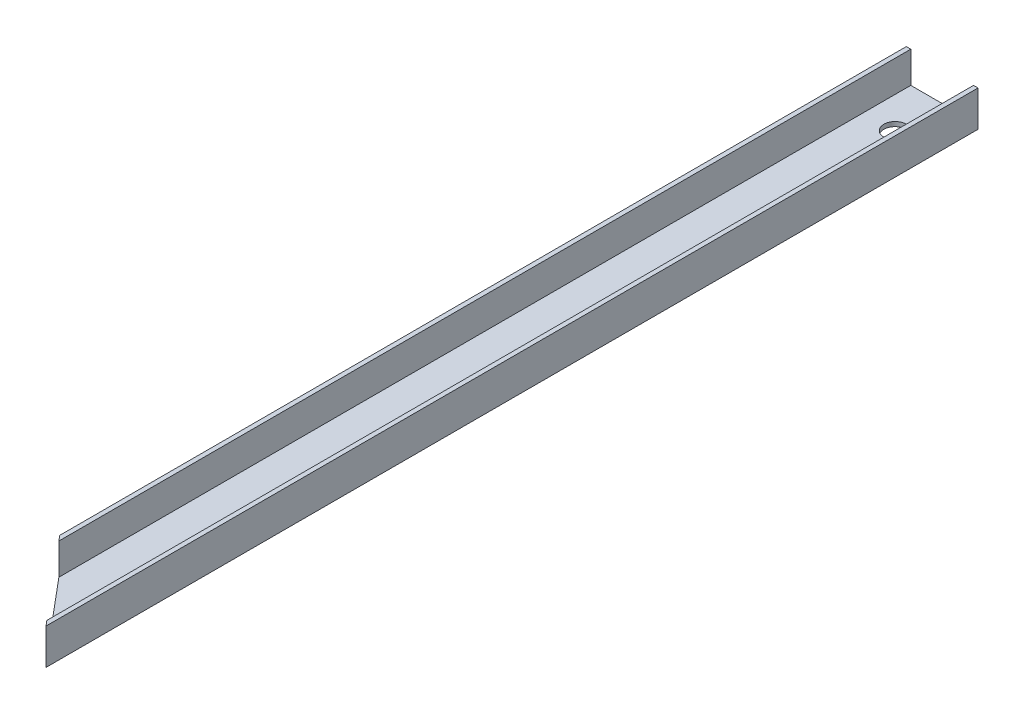
SolidWorks part; units mm, degrees
ref_plane "Front Plane" through (0, 0, 0) normal (0, 0, 1) x (1, 0, 0)
ref_plane "Top Plane" through (0, 0, 0) normal (0, 1, 0) x (1, 0, 0)
ref_plane "Right Plane" through (0, 0, 0) normal (1, 0, 0) x (0, 0, -1)
sketch "Sketch1" plane through (0, 0, 0) normal (0, 0, 1) x (1, 0, 0)
  line L0 (-22.225, -9.525) -> (-22.225, 12.7)
  line L1 (-25.4, -12.7) -> (25.4, -12.7)
  line L2 (-25.4, -12.7) -> (-25.4, 12.7)
  line L3 (-22.225, -9.525) -> (22.225, -9.525)
  line L4 (25.4, -12.7) -> (25.4, 12.7)
  line L5 (22.225, -9.525) -> (22.225, 12.7)
  line L6 (-25.4, 12.7) -> (-22.225, 12.7)
  line L7 (25.4, 12.7) -> (22.225, 12.7)
  dimension "D1" = 25.4
  dimension "D2" = 50.8
  dimension "D3" = 3.175
extrude "Boss-Extrude1" add sketch "Sketch1" along normal blind 660.4
sketch "Sketch2" plane through (0, -12.7, 0) normal (0, -1, 0) x (1, 0, 0)
  line L0 (25.4, 660.4) -> (-25.4, 599.8589)
  line L1 (-25.4, 660.4) -> (-25.4, 0) construction
  line L2 (-25.4, 599.8589) -> (-25.4, 660.4)
  line L3 (-25.4, 660.4) -> (25.4, 660.4)
  dimension "D1" = 50
extrude "Cut-Extrude1" cut sketch "Sketch2" against normal through all
sketch "Sketch3" plane through (0, -12.7, 0) normal (0, -1, 0) x (1, 0, 0)
  line L0 (0, 0) -> (0, 25.4) construction
  line L1 (-25.4, 0) -> (25.4, 0) construction
  circle A0 centre (0, 33.3375) radius 7.9375
  dimension "D1" = 25.4
extrude "Cut-Extrude2" cut sketch "Sketch3" against normal up to next
